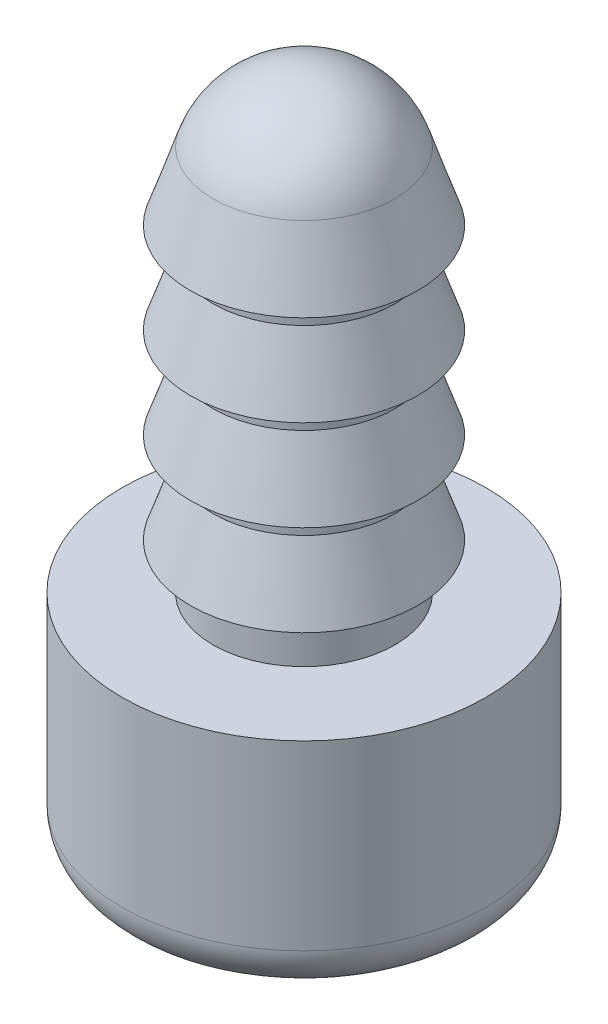
SolidWorks part; units mm, degrees
ref_plane "前视基准面" through (0, 0, 0) normal (0, 0, 1) x (1, 0, 0)
ref_plane "上视基准面" through (0, 0, 0) normal (0, 1, 0) x (1, 0, 0)
ref_plane "右视基准面" through (0, 0, 0) normal (1, 0, 0) x (0, 0, -1)
other "Configuration Table"
sketch "草图1" plane through (0, 0, 0) normal (0, 0, 1) x (1, 0, 0)
  line L0 (0, 1) -> (0, -28.883)
  line L1 (4, -18.883) -> (8, -18.883)
  line L2 (8, -18.883) -> (8, -28.883)
  line L3 (4, -1.883) -> (5, -4.883)
  line L4 (5, -4.883) -> (4, -3.883)
  line L5 (4, -3.883) -> (4, -5.883)
  line L6 (4, -5.883) -> (5, -8.883)
  line L7 (5, -8.883) -> (4, -7.883)
  line L8 (4, -7.883) -> (4, -9.883)
  line L9 (4, -9.883) -> (5, -12.883)
  line L10 (5, -12.883) -> (4, -11.883)
  line L11 (4, -11.883) -> (4, -13.883)
  line L12 (4, -13.883) -> (5, -16.883)
  line L13 (5, -16.883) -> (4, -15.883)
  line L14 (4, -15.883) -> (4, -18.883)
  line L16 (0, 13.4074) -> (0, -15.0512) construction
  line L17 (8, -28.883) -> (0, -28.883)
  arc A0 (4, -1.883) -> (0, 1) centre (0, -3.2164) ccw
  point P0 (4, -12.883)
  point P19 (0, 0)
  point P21 (0, 0)
  point P22 (0, 0)
  dimension "D17" = 10
  dimension "D2" = 1
  dimension "D3" = 4
  dimension "D4" = 1
  dimension "D5" = 4
  dimension "D6" = 4
  dimension "D7" = 4
  dimension "D8" = 4
  dimension "D9" = 1
  dimension "D10" = 2
  dimension "D11" = 2
  dimension "D12" = 1
  dimension "D13" = 2
  dimension "D14" = 1
  dimension "D15" = 2
  dimension "D16" = 2
  dimension "D18" = 8
  dimension "D19" = 45
revolve "旋转1" add sketch "草图1" angle 360 about L16
fillet "圆角1" radius 2 1 edges at (0, -28.883, 8)
